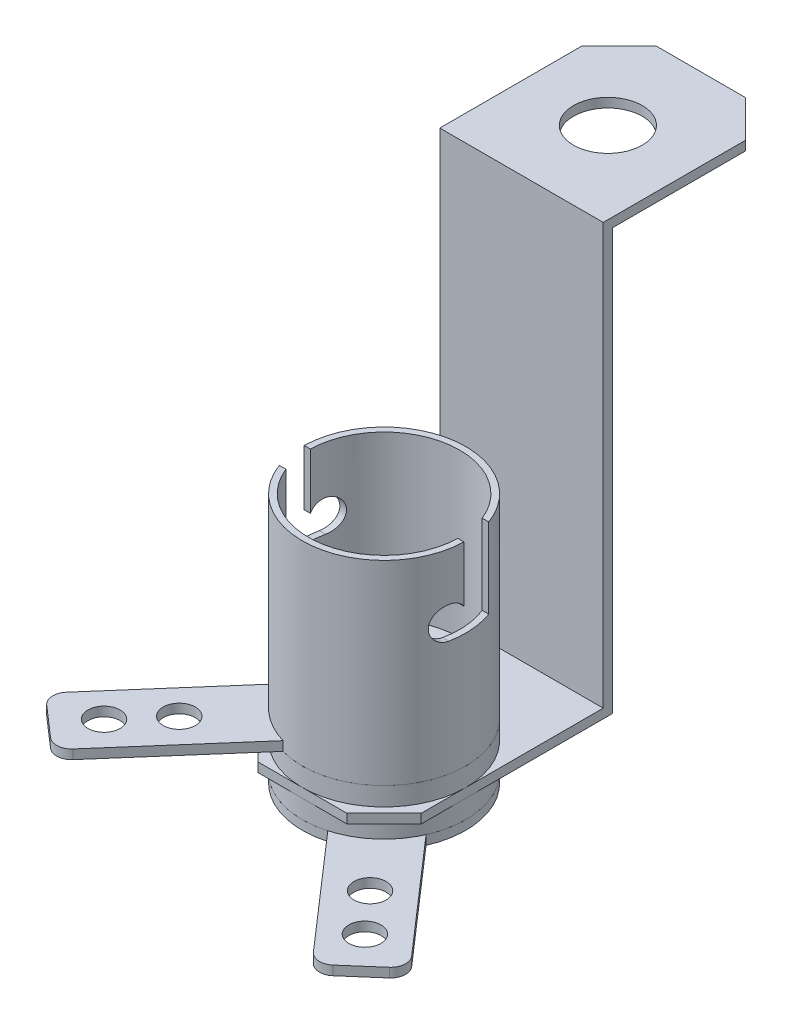
SolidWorks part; units mm, degrees
ref_plane "Front Plane" through (0, 0, 0) normal (0, 0, 1) x (1, 0, 0)
ref_plane "Top Plane" through (0, 0, 0) normal (0, 1, 0) x (1, 0, 0)
ref_plane "Right Plane" through (0, 0, 0) normal (1, 0, 0) x (0, 0, -1)
sketch "Sketch1" plane through (0, 0, 0) normal (0, 1, 0) x (1, 0, 0)
  line L0 (-3.048, 0) -> (3.048, 0)
  line L1 (3.048, 0) -> (5.588, -2.54)
  line L2 (5.588, -2.54) -> (5.588, -12.2555)
  line L3 (-3.048, 0) -> (-5.588, -2.54)
  line L4 (-5.588, -2.54) -> (-5.588, -12.2555)
  line L5 (0, 0) -> (0, -12.2555) construction
  line L6 (-5.588, -12.2555) -> (5.588, -12.2555)
  circle A0 centre (0, -6.35) radius 2.3495
  point P6 (0, 0)
  point P10 (0, 0)
  dimension "D1" = 4.699
  dimension "D2" = 11.176
  dimension "D3" = 12.2555
  dimension "D4" = 2.54
  dimension "D5" = 2.54
  dimension "D6" = 6.35
extrude "Boss-Extrude1" add sketch "Sketch1" against normal blind 0.635
sketch "Sketch2" plane through (0, -0.635, 0) normal (0, -1, 0) x (1, 0, 0)
  line L0 (5.588, 12.2555) -> (5.588, 2.54) construction
  line L1 (-5.588, 12.2555) -> (5.588, 12.2555)
  line L2 (-5.588, 12.2555) -> (-5.588, 11.6205)
  line L3 (-5.588, 11.6205) -> (5.588, 11.6205)
  line L4 (5.588, 12.2555) -> (5.588, 11.6205)
  dimension "D1" = 0.635
extrude "Boss-Extrude2" add sketch "Sketch2" along normal blind 28.7655
sketch "Sketch3" plane through (0, 0, 12.2555) normal (0, 0, 1) x (1, 0, 0)
  line L0 (5.588, -29.4005) -> (5.588, 0) construction
  line L1 (-5.588, -29.4005) -> (5.588, -29.4005)
  line L2 (-5.588, -29.4005) -> (-5.588, -28.7655)
  line L3 (-5.588, -28.7655) -> (5.588, -28.7655)
  line L4 (5.588, -29.4005) -> (5.588, -28.7655)
  dimension "D1" = 0.635
extrude "Boss-Extrude3" add sketch "Sketch3" along normal blind 14.986
sketch "Sketch4" plane through (0, -28.7655, 0) normal (0, 1, 0) x (1, 0, 0)
  line L2 (5.588, -27.2415) -> (-5.588, -27.2415) construction
  line L6 (-5.588, -24.7015) -> (-3.048, -27.2415)
  line L7 (-5.588, -27.2415) -> (-5.588, -12.2555) construction
  line L8 (-3.048, -27.2415) -> (-5.588, -27.2415)
  line L9 (-5.588, -27.2415) -> (-5.588, -24.7015)
  line L10 (5.588, -27.2415) -> (5.588, -24.7015)
  line L11 (5.588, -27.2415) -> (5.588, -12.2555) construction
  line L12 (5.588, -24.7015) -> (3.048, -27.2415)
  line L13 (3.048, -27.2415) -> (5.588, -27.2415)
  line L14 (0, -12.2555) -> (0, -27.2415) construction
  line L15 (5.588, -12.2555) -> (-5.588, -12.2555) construction
  dimension "D1" = 2.54
  dimension "D2" = 2.54
extrude "Cut-Extrude1" cut sketch "Sketch4" against normal through all
sketch "Sketch5" plane through (0, -28.7655, 0) normal (0, 1, 0) x (1, 0, 0)
  line L0 (3.048, -27.2415) -> (-3.048, -27.2415) construction
  line L1 (-5.588, -24.7015) -> (-5.588, -12.2555) construction
  circle A0 centre (0, -21.6535) radius 5.588
  point P4 (0, -27.2415)
extrude "Boss-Extrude4" add sketch "Sketch5" along normal blind 1.27 separate body
sketch "Sketch6" plane through (0, -27.4955, 0) normal (0, 1, 0) x (1, 0, 0)
  line L0 (-11.8103, -31.5755) -> (-5.117, -23.8989)
  line L1 (-11.7122, -33.009) -> (-9.6541, -34.8034)
  line L2 (-8.2206, -34.7053) -> (-1.5274, -27.0287)
  line L3 (0, -21.6535) -> (-10.6831, -33.9062) construction
  line L4 (-5.4672, -24.3005) -> (-1.8775, -27.4303) construction
  line L5 (3.048, -27.2415) -> (-3.048, -27.2415) construction
  line L6 (-9.6399, -32.7096) -> (-10.6831, -33.9062) construction
  line L7 (0, -27.2415) -> (0, -12.2555) construction
  line L8 (5.588, -12.2555) -> (-5.588, -12.2555) construction
  line L9 (9.6399, -32.7096) -> (10.6831, -33.9062) construction
  line L10 (5.4672, -24.3005) -> (1.8775, -27.4303) construction
  line L11 (8.2206, -34.7053) -> (1.5274, -27.0287) construction
  line L12 (11.7122, -33.009) -> (9.6541, -34.8034) construction
  line L13 (11.8103, -31.5755) -> (5.117, -23.8989) construction
  circle A0 centre (0, -21.6535) radius 5.588 construction
  circle A1 centre (0, -21.6535) radius 5.588
  arc A2 (-1.5274, -27.0287) -> (-5.117, -23.8989) centre (0, -21.6535) ccw
  circle A3 centre (-8.9179, -31.8816) radius 1.0985
  circle A4 centre (-6.5225, -29.1343) radius 1.0985
  arc A5 (-9.6541, -34.8034) -> (-8.2206, -34.7053) centre (-8.9864, -34.0376) ccw
  arc A6 (-11.8103, -31.5755) -> (-11.7122, -33.009) centre (-11.0445, -32.2432) ccw
  arc A7 (11.8103, -31.5755) -> (11.7122, -33.009) centre (11.0445, -32.2432) cw construction
  arc A8 (9.6541, -34.8034) -> (8.2206, -34.7053) centre (8.9864, -34.0376) cw construction
  circle A9 centre (6.5225, -29.1343) radius 1.0985 construction
  circle A10 centre (8.9179, -31.8816) radius 1.0986 construction
  point P20 (-8.8883, -35.4711)
  point P23 (-12.478, -32.3413)
  point P44 (12.478, -32.3413)
  point P45 (8.8883, -35.4711)
  dimension "D7" = 2.1971
  dimension "D8" = 1.016
  dimension "D2" = 10.668
  dimension "D3" = 8.2296
  dimension "D4" = 4.7625
  dimension "D5" = 3.6449
  dimension "D6" = 1.5875
  dimension "D1" = 0
extrude "Boss-Extrude5" add sketch "Sketch6" along normal blind 0.635 separate body
sketch "Sketch7" plane through (0, -29.4005, 0) normal (0, 1, 0) x (1, 0, 0)
  circle A0 centre (0, -21.6535) radius 5.588
  arc A1 (-1.5274, -27.0287) -> (-5.117, -23.8989) centre (0, -21.6535) ccw construction
extrude "Boss-Extrude6" add sketch "Sketch7" against normal blind 1.27 separate body
sketch "Sketch8" plane through (0, -30.6705, 0) normal (0, 1, 0) x (1, 0, 0)
  line L0 (11.7122, -33.009) -> (9.6541, -34.8034) construction
  line L1 (11.8103, -31.5755) -> (5.117, -23.8989) construction
  line L2 (8.2206, -34.7053) -> (1.5274, -27.0287) construction
  line L3 (11.7122, -33.009) -> (9.6541, -34.8034)
  line L4 (11.8103, -31.5755) -> (5.117, -23.8989)
  line L5 (8.2206, -34.7053) -> (1.5274, -27.0287)
  arc A0 (5.117, -23.8989) -> (1.5274, -27.0287) centre (0, -21.6535) ccw
  circle A1 centre (6.5225, -29.1343) radius 1.0985 construction
  circle A2 centre (8.9179, -31.8816) radius 1.0986 construction
  arc A3 (8.2206, -34.7053) -> (9.6541, -34.8034) centre (8.9864, -34.0376) ccw construction
  arc A4 (11.7122, -33.009) -> (11.8103, -31.5755) centre (11.0445, -32.2432) ccw construction
  circle A5 centre (6.5225, -29.1343) radius 1.0985
  circle A6 centre (8.9179, -31.8816) radius 1.0986
  arc A7 (8.2206, -34.7053) -> (9.6541, -34.8034) centre (8.9864, -34.0376) ccw
  arc A8 (11.7122, -33.009) -> (11.8103, -31.5755) centre (11.0445, -32.2432) ccw
  arc A9 (-1.5274, -27.0287) -> (-5.117, -23.8989) centre (0, -21.6535) ccw construction
extrude "Boss-Extrude7" add sketch "Sketch8" against normal blind 0.635 separate body
sketch "Sketch9" plane through (0, -26.8605, 0) normal (0, -1, 0) x (-1, 0, 0)
  circle A0 centre (0, -21.6535) radius 5.588
  arc A1 (-1.5274, -27.0287) -> (-5.117, -23.8989) centre (0, -21.6535) ccw construction
  circle A2 centre (0, -21.6535) radius 5.1689
  dimension "D1" = 0.4191
extrude "Boss-Extrude8" add sketch "Sketch9" against normal blind 12.7
sketch "Sketch10" plane through (0, -26.8605, 0) normal (0, -1, 0) x (-1, 0, 0)
  circle A2 centre (0, -21.6535) radius 5.1689
  circle A3 centre (0, -21.6535) radius 5.1689 construction
extrude "Boss-Extrude9" add sketch "Sketch10" against normal offset from surface (1.6002 mm away) 11.0998 up to face at (0, -14.1605, 16.4846)
sketch "Sketch11" plane through (0, 0, 0) normal (1, 0, 0) x (0, 0, -1)
  line L0 (-19.7485, -14.1605) -> (-19.7485, -19.6215)
  line L1 (-16.4846, -14.1605) -> (-26.8224, -14.1605) construction
  line L2 (-19.7485, -19.6215) -> (-22.7077, -19.6215)
  line L3 (-21.7805, -17.9705) -> (-21.7805, -14.1605)
  line L4 (-21.7805, -14.1605) -> (-19.7485, -14.1605)
  line L5 (-23.7935, -18.5357) -> (-19.7485, -18.5357) construction
  line L6 (-16.0655, -27.4955) -> (-16.0655, -14.1605) construction
  arc A1 (-21.7805, -17.9705) -> (-22.7077, -19.6215) centre (-22.7077, -18.5357) ccw
  point P7 (-23.7282, -17.9705)
  dimension "D2" = 2.1717
  dimension "D1" = 2.032
  dimension "D3" = 3.81
  dimension "D4" = 5.461
  dimension "D5" = 3.683
extrude "Cut-Extrude2" cut sketch "Sketch11" along normal through all
ref_axis "Axis1" through (0, -14.1605, 21.6535) along (0, -1, 0)
pattern_circular "CirPattern1" count 2 over 360 about axis through (0, -14.1605, 21.6535) along (0, -1, 0) of "Cut-Extrude2"
